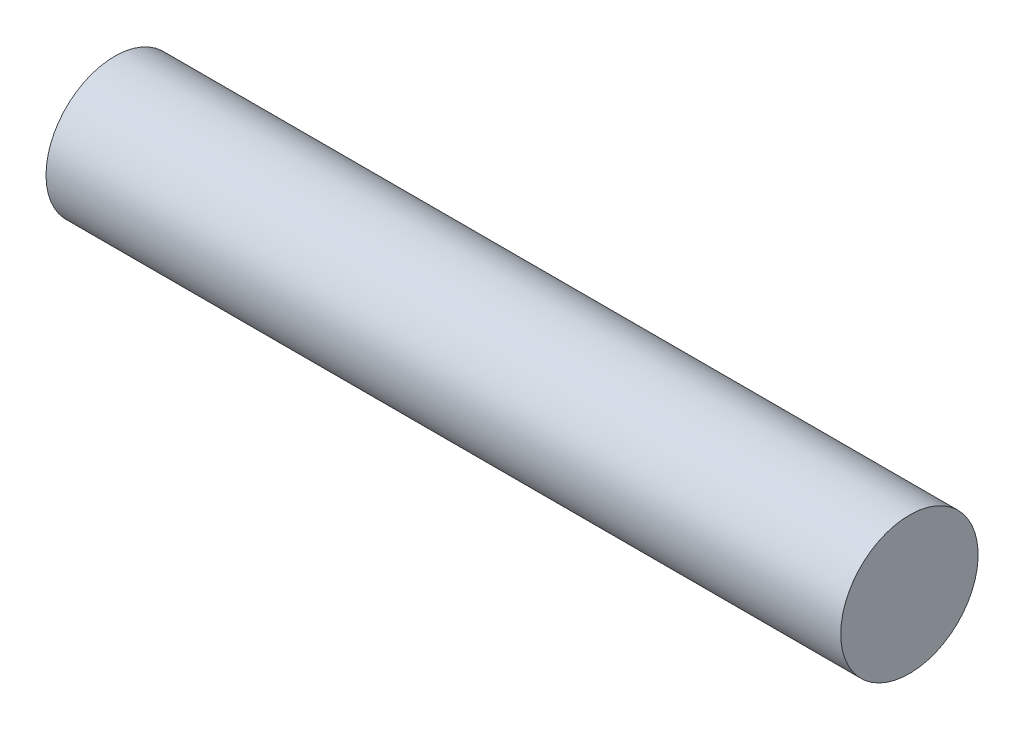
SolidWorks part; units mm, degrees
ref_plane "前视基准面" through (0, 0, 0) normal (0, 0, 1) x (1, 0, 0)
ref_plane "上视基准面" through (0, 0, 0) normal (0, 1, 0) x (1, 0, 0)
ref_plane "右视基准面" through (0, 0, 0) normal (1, 0, 0) x (0, 0, -1)
other "Configuration Table"
sketch "草图1" plane through (0, 0, 0) normal (0, 0, 1) x (1, 0, 0)
  line L0 (0, 0) -> (40.0305, 0) construction
  line L1 (0, 0) -> (0, 7)
  line L2 (0, 7) -> (81, 7)
  line L3 (81, 7) -> (81, 0)
  line L4 (0, 0) -> (81, 0)
  dimension "D1" = 7
  dimension "D2" = 81
revolve "旋转1" add sketch "草图1" angle 360 about L0
